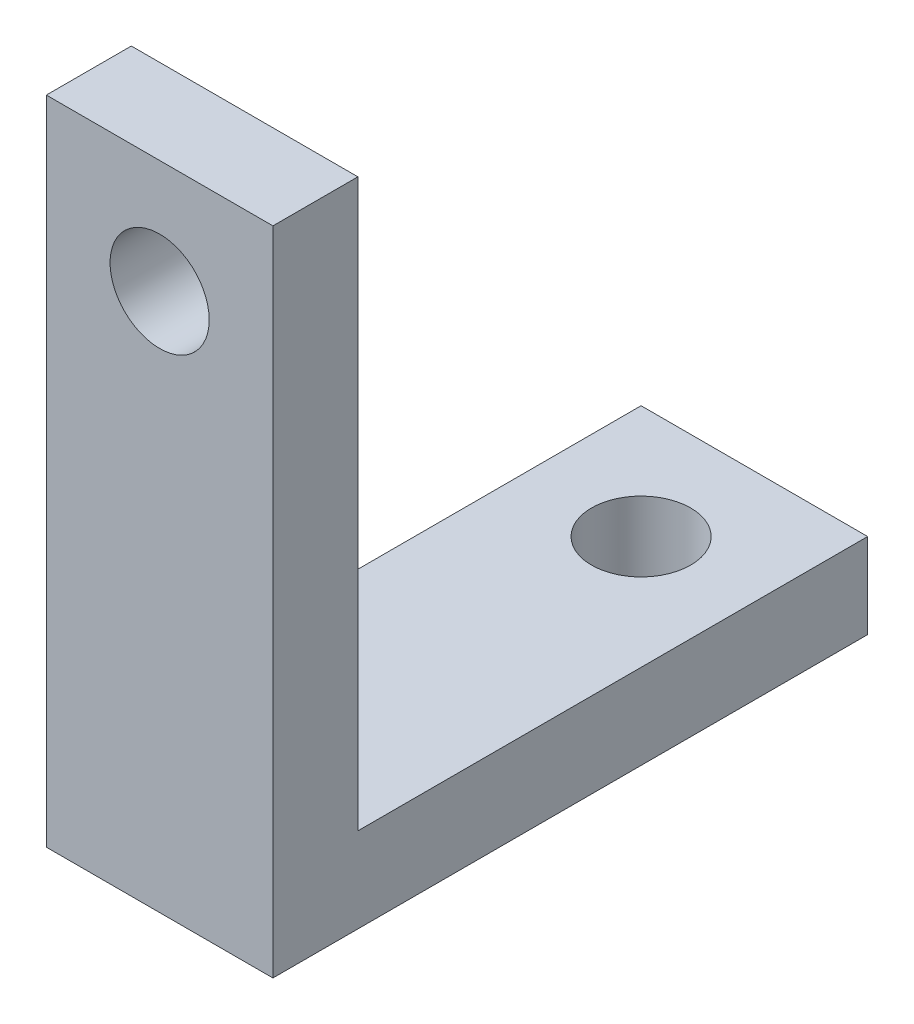
SolidWorks part; units mm, degrees
ref_plane "Front Plane" through (0, 0, 0) normal (0, 0, 1) x (1, 0, 0)
ref_plane "Top Plane" through (0, 0, 0) normal (0, 1, 0) x (1, 0, 0)
ref_plane "Right Plane" through (0, 0, 0) normal (1, 0, 0) x (0, 0, -1)
sketch "Sketch1" plane through (0, 0, 0) normal (0, 0, 1) x (1, 0, 0)
  line L1 (-52.2175, 17.1569) -> (-44.2175, 17.1569)
  line L2 (-52.2175, 17.1569) -> (-52.2175, -5.8431)
  line L3 (-52.2175, -5.8431) -> (-44.2175, -5.8431)
  line L4 (-44.2175, 17.1569) -> (-44.2175, -5.8431)
extrude "Boss-Extrude1" add sketch "Sketch1" along normal blind 3
sketch "Sketch2" plane through (0, 0, 0) normal (0, 0, -1) x (-1, 0, 0)
  line L0 (52.2175, -5.8431) -> (44.2175, -5.8431)
  line L1 (44.2175, -5.8431) -> (44.2175, -2.8431)
  line L2 (44.2175, -5.8431) -> (44.2175, 17.1569) construction
  line L3 (44.2175, -2.8431) -> (52.2175, -2.8431)
  line L4 (52.2175, 17.1569) -> (52.2175, -5.8431) construction
  line L5 (52.2175, -2.8431) -> (52.2175, -5.8431)
extrude "Boss-Extrude2" add sketch "Sketch2" along normal blind 18
sketch "Sketch3" plane through (0, -5.8431, 0) normal (0, -1, 0) x (-1, 0, 0)
  line L0 (48.2175, 14) -> (48.2175, 18) construction
  line L3 (44.2175, 18) -> (52.2175, 18) construction
  circle A0 centre (48.2175, 14) radius 1.75
extrude "Cut-Extrude1" cut sketch "Sketch3" against normal blind 8
sketch "Sketch4" plane through (0, 0, 3) normal (0, 0, 1) x (1, 0, 0)
  line L0 (-48.2175, 17.1569) -> (-48.2175, 9.1569) construction
  line L1 (-44.2175, 17.1569) -> (-52.2175, 17.1569) construction
  circle A0 centre (-48.2175, 13.1569) radius 1.75
extrude "Cut-Extrude2" cut sketch "Sketch4" against normal blind 8
